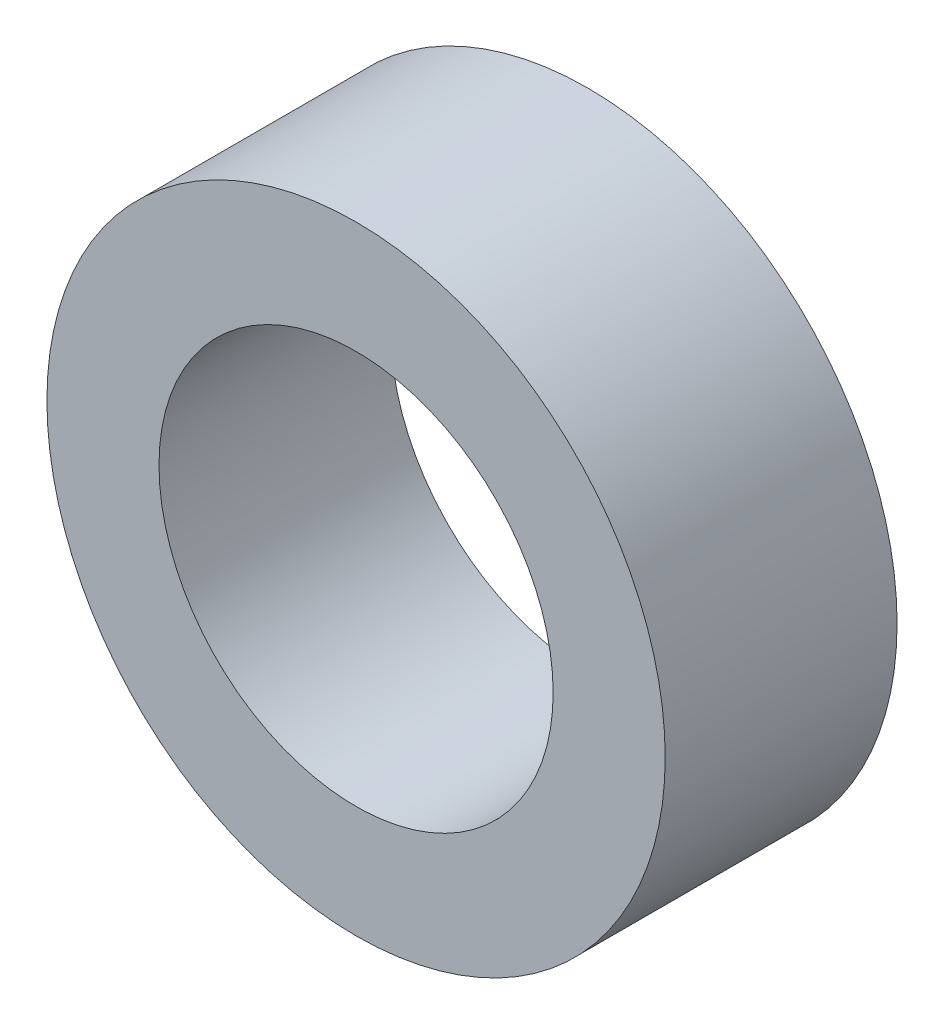
SolidWorks part; units mm, degrees
material "ABS"
ref_plane "Płaszczyzna przednia" through (0, 0, 0) normal (0, 0, 1) x (1, 0, 0)
ref_plane "Płaszczyzna górna" through (0, 0, 0) normal (0, 1, 0) x (1, 0, 0)
ref_plane "Płaszczyzna prawa" through (0, 0, 0) normal (1, 0, 0) x (0, 0, -1)
sketch "Szkic1" plane through (0, 0, 0) normal (0, 0, 1) x (1, 0, 0)
  circle A0 centre (0, 0) radius 5.1
  circle A1 centre (0, 0) radius 8
  dimension "D1" = 10.2
  dimension "D2" = 16
extrude "Dodanie-wyciągnięcie1" add sketch "Szkic1" along normal blind 6
